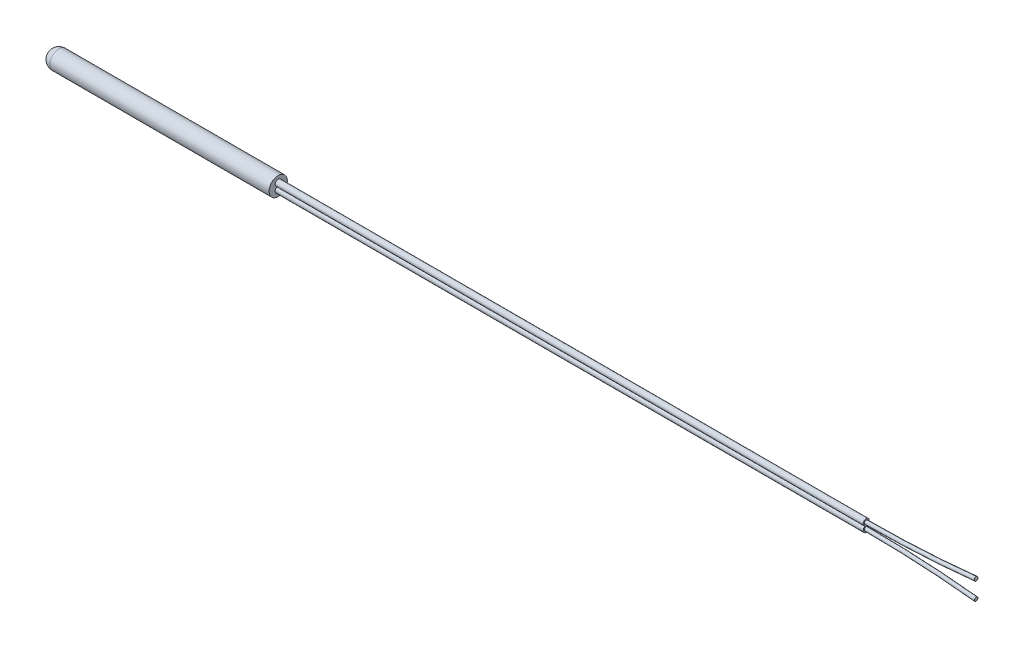
SolidWorks part; units mm, degrees
ref_plane "Front" through (0, 0, 0) normal (0, 0, 1) x (1, 0, 0)
ref_plane "Top" through (0, 0, 0) normal (0, 1, 0) x (1, 0, 0)
ref_plane "Right" through (0, 0, 0) normal (1, 0, 0) x (0, 0, -1)
sketch "Sketch1" plane through (0, 0, 0) normal (0, 0, 1) x (1, 0, 0)
  line L0 (0, 0) -> (9.525, 0)
  line L1 (9.525, 0.381) -> (9.525, 0)
  line L2 (0, 0) -> (15.1271, 0) construction
  line L3 (9.525, 0.381) -> (0.381, 0.381)
  arc A0 (0.381, 0.381) -> (0, 0) centre (0.381, 0) ccw
  dimension "D1" = 9.525
  dimension "D2" = 0.762
revolve "Revolve1" add sketch "Sketch1" angle 360 about L2
sketch "Sketch2" plane through (9.525, 0, 0) normal (1, 0, 0) x (0, 0, -1)
  line L0 (0, 0) -> (-0.5429, 0) construction
  arc A0 (0.036, 0) -> (-0.036, 0) centre (0, 0.1218) ccw
  arc A1 (0.036, 0) -> (-0.036, 0) centre (0, -0.1218) cw
  dimension "D1" = 0.127
sketch "Sketch3" plane through (0, 0, 0) normal (0, 1, 0) x (1, 0, 0)
  line L0 (9.525, 0) -> (9.6674, 0)
  line L1 (9.525, 0) -> (9.525, -0.5429) construction
  line L2 (9.6674, 0) -> (9.8606, 0)
  line L5 (9.8606, 0) -> (34.0396, 0)
  point P8 (10.033, 0)
sweep "Sweep1" add profiles "Sketch2" path "Sketch3"
sketch "Sketch4" plane through (34.0396, 0, 0) normal (1, 0, 0) x (0, 0, -1)
  circle A0 centre (0, -0.1218) radius 0.0777
  dimension "D1" = 0.1554
sketch "Sketch5" plane through (0, 0, 0) normal (0, 0, 1) x (1, 0, 0)
  line L0 (34.0396, -0.1995) -> (34.0396, -0.0441) construction
  line L2 (9.525, -0.1218) -> (34.0396, -0.1218) construction
  line L4 (34.0396, -0.2488) -> (34.0396, 0) construction
  arc A0 (34.0396, -0.1218) -> (38.6222, -0.3682) centre (34.0396, -42.8609) cw
  dimension "D1" = 0.2464
  dimension "D2" = 4.5826
sweep "Sweep2" add profiles "Sketch4" path "Sketch5"
mirror "Mirror1" about plane through (0, 0, 0) normal (0, 1, 0) of "Sweep2"
sketch "Sketch6" [suppressed] plane through (0, 0, 0) normal (0, 1, 0) x (1, 0, 0)
  line L1 (11.0044, 1.3235) -> (24.2443, 1.3235)
  line L2 (11.0044, 1.3235) -> (11.0044, -1.2535)
  line L3 (11.0044, -4.7455) -> (24.2443, -4.7455)
  line L4 (24.2443, 1.3235) -> (24.2443, -4.7455)
  line L5 (11.0044, -1.2535) -> (1.0775, -1.2535)
  line L7 (11.0044, -4.7455) -> (1.0775, -4.7455)
  line L8 (1.0775, -1.2535) -> (1.0775, -4.7455)
extrude "Cut-Extrude1" [suppressed] cut sketch "Sketch6" along normal mid plane 2.54
